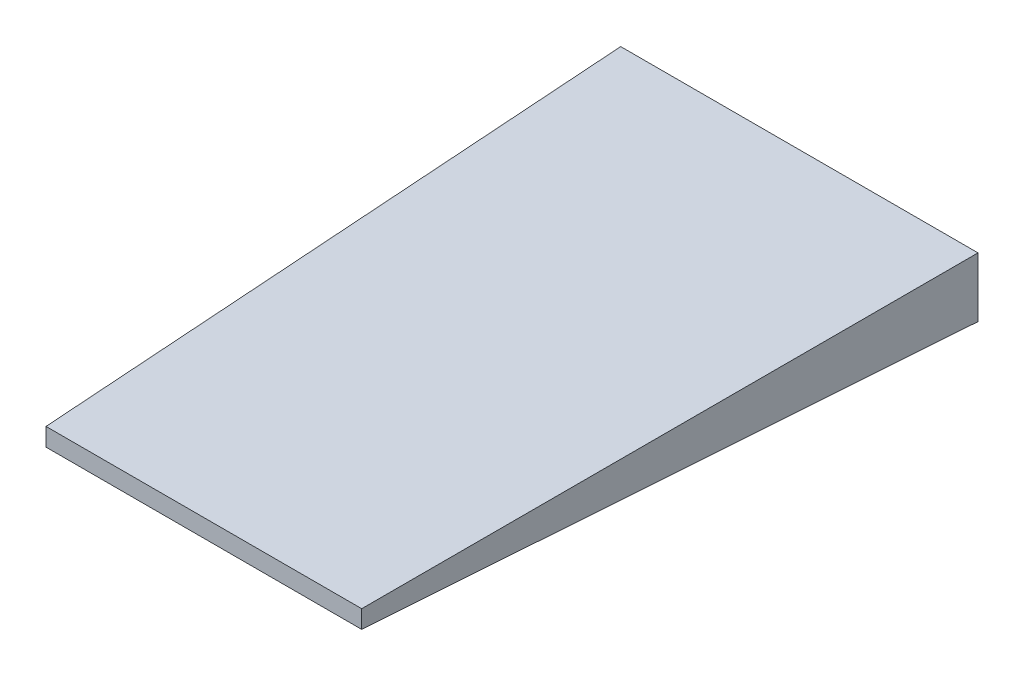
SolidWorks part; units mm, degrees
ref_plane "Front Plane" through (0, 0, 0) normal (0, 0, 1) x (1, 0, 0)
ref_plane "Top Plane" through (0, 0, 0) normal (0, 1, 0) x (1, 0, 0)
ref_plane "Right Plane" through (0, 0, 0) normal (1, 0, 0) x (0, 0, -1)
sketch "Sketch1" plane through (0, 0, 0) normal (0, 0, 1) x (1, 0, 0)
  line L1 (-76.2, -12.7) -> (76.2, -12.7)
  line L2 (-76.2, -12.7) -> (-76.2, 12.7)
  line L3 (-76.2, 12.7) -> (76.2, 12.7)
  line L4 (76.2, -12.7) -> (76.2, 12.7)
  line L5 (-76.2, -12.7) -> (76.2, 12.7) construction
  line L6 (-76.2, 12.7) -> (76.2, -12.7) construction
  point P0 (0, 0)
  dimension "D1" = 152.4
  dimension "D2" = 25.4
extrude "Boss-Extrude1" add sketch "Sketch1" along normal blind 254 draft 2 contours L2 L1 L4 L3
